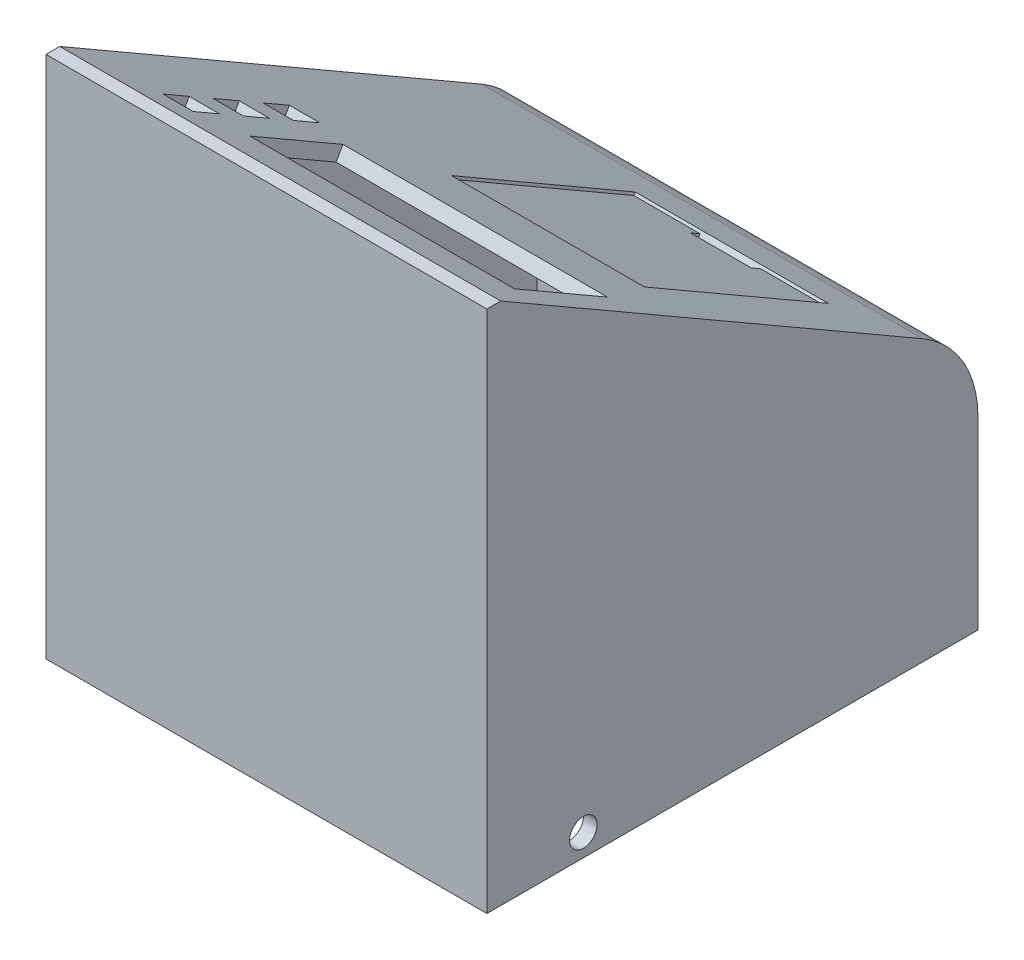
SolidWorks part; units mm, degrees
ref_plane "Front Plane" through (0, 0, 0) normal (0, 0, 1) x (1, 0, 0)
ref_plane "Top Plane" through (0, 0, 0) normal (0, 1, 0) x (1, 0, 0)
ref_plane "Right Plane" through (0, 0, 0) normal (1, 0, 0) x (0, 0, -1)
sketch "Sketch1" plane through (0, 0, 0) normal (1, 0, 0) x (0, 0, -1)
  line L0 (0, 0) -> (173.2051, -100)
  line L1 (173.2051, -100) -> (173.2051, -190)
  line L2 (173.2051, -190) -> (0, -190)
  line L3 (0, -190) -> (0, 0)
  line L4 (173.2051, -100) -> (290.6561, -100) construction
  dimension "D1" = 90
  dimension "D2" = 200
  dimension "D3" = 150
extrude "Boss-Extrude1" add sketch "Sketch1" along normal blind 5
ref_plane "Plane1" through (0, 0, 0) normal (0, 0.866, -0.5) x (1, 0, 0)
sketch "Sketch2" plane through (0, 0, 0) normal (0, 0.866, -0.5) x (1, 0, 0)
  line L0 (0, 200) -> (160, 200)
  line L1 (0, 200) -> (0, 0) construction
  line L2 (5, 200) -> (0, 200) construction
  line L3 (0, 200) -> (0, 0)
  line L4 (0, 0) -> (160, 0)
  line L5 (160, 0) -> (160, 200)
  dimension "D1" = 160
  dimension "D2" = 160
extrude "Boss-Extrude2" add sketch "Sketch2" against normal blind 5 contours L4 L5 L0 L3
ref_plane "Plane3" through (0, 0, 0) normal (0, 0, 1) x (1, 0, 0)
sketch "Sketch4" plane through (0, 0, 0) normal (0, 0, 1) x (1, 0, 0)
  line L0 (0, 0) -> (160, 0)
  line L1 (160, 0) -> (160, -190)
  line L2 (0, 0) -> (0, -190)
  line L3 (5, -190) -> (0, -190) construction
  line L4 (0, -190) -> (160, -190)
extrude "Boss-Extrude4" add sketch "Sketch4" along normal blind 5
ref_plane "Plane4" through (0, 0, -173.2051) normal (0, 0, -1) x (-1, 0, 0)
sketch "Sketch5" plane through (0, 0, -173.2051) normal (0, 0, -1) x (-1, 0, 0)
  line L0 (0, -100) -> (-160, -100)
  line L1 (-5, -100) -> (0, -100) construction
  line L2 (-160, -100) -> (-160, -190)
  line L3 (-160, -190) -> (0, -190)
  line L4 (0, -190) -> (0, -100)
extrude "Boss-Extrude5" add sketch "Sketch5" against normal blind 5
ref_plane "Plane5" through (70, 0, 0) normal (-1, 0, 0) x (0, 0, 1)
ref_plane "Plane6" through (80, 0, 0) normal (-1, 0, 0) x (0, 0, 1)
mirror "Mirror1" about plane through (80, 0, 0) normal (-1, 0, 0) of "Boss-Extrude1"
ref_plane "Plane7" through (0, 0, 0) normal (0, 0.866, -0.5) x (1, 0, 0)
sketch "Sketch6" plane through (0, 0, 0) normal (0, 0.866, -0.5) x (1, 0, 0)
  line L0 (0, 200) -> (0, 0) construction
  line L1 (160, 0) -> (0, 0) construction
  line L2 (160, 0) -> (160, 200) construction
  line L3 (160, 200) -> (0, 200) construction
  line L4 (0, 200) -> (0, 0) construction
  line L5 (160, 0) -> (0, 0) construction
  line L6 (160, 0) -> (160, 200) construction
  line L7 (160, 200) -> (0, 200) construction
  line L8 (34, 7.7765) -> (34, 64.7725) construction
  line L11 (54, 10) -> (150, 10) construction
  line L12 (150, 49) -> (150, 10) construction
  line L14 (54, 56.3152) -> (150, 56.3152)
  line L17 (28.5, 21.3152) -> (39.5, 21.3152)
  line L18 (28.5, 21.3152) -> (28.5, 10.3152)
  line L19 (28.5, 10.3152) -> (39.5, 10.3152)
  line L20 (39.5, 21.3152) -> (39.5, 10.3152)
  line L21 (28.5, 21.3152) -> (39.5, 10.3152) construction
  line L22 (28.5, 10.3152) -> (39.5, 21.3152) construction
  line L23 (28.5, 42.3152) -> (39.5, 42.3152)
  line L24 (28.5, 42.3152) -> (28.5, 31.3152)
  line L25 (28.5, 31.3152) -> (39.5, 31.3152)
  line L26 (39.5, 42.3152) -> (39.5, 31.3152)
  line L27 (28.5, 42.3152) -> (39.5, 31.3152) construction
  line L28 (28.5, 31.3152) -> (39.5, 42.3152) construction
  line L29 (28.5, 63.3152) -> (39.5, 63.3152)
  line L30 (28.5, 63.3152) -> (28.5, 52.3152)
  line L31 (28.5, 52.3152) -> (39.5, 52.3152)
  line L32 (39.5, 63.3152) -> (39.5, 52.3152)
  line L33 (28.5, 63.3152) -> (39.5, 52.3152) construction
  line L34 (28.5, 52.3152) -> (39.5, 63.3152) construction
  line L35 (54, 56.3152) -> (54, 17.3152)
  line L36 (54, 17.3152) -> (150, 17.3152)
  line L37 (150, 56.3152) -> (150, 17.3152)
  line L38 (54, 56.3152) -> (150, 17.3152) construction
  line L39 (54, 17.3152) -> (150, 56.3152) construction
  point P6 (102, 36.8152)
  point P11 (34, 15.8152)
  point P17 (34, 36.8152)
  point P22 (34, 57.8152)
  dimension "D2" = 96
  dimension "D3" = 10
  dimension "D4" = 10
  dimension "D5" = 39
  dimension "D6" = 11
  dimension "D7" = 11
  dimension "D8" = 11
  dimension "D9" = 11
  dimension "D10" = 10
  dimension "D11" = 10
extrude "Cut-Extrude2" cut sketch "Sketch6" against normal blind 5
fillet "Fillet1" radius 40 1 edges at (80, -100, -173.2051)
sketch "Sketch7" plane through (0, 0, 0) normal (0, 0.866, -0.5) x (1, 0, 0)
  line L0 (34, 63.3152) -> (160, 63.3152) construction
  line L1 (39.5, 63.3152) -> (28.5, 63.3152) construction
  line L2 (160, 0) -> (160, 176.906) construction
  line L4 (70, 160.3152) -> (140, 160.3152)
  line L5 (70, 160.3152) -> (70, 83.3152)
  line L6 (70, 83.3152) -> (140, 83.3152)
  line L7 (140, 160.3152) -> (140, 83.3152)
  line L8 (70, 160.3152) -> (140, 83.3152) construction
  line L9 (70, 83.3152) -> (140, 160.3152) construction
  point P6 (105, 121.8152)
  dimension "D1" = 70
  dimension "D2" = 77
  dimension "D3" = 20
  dimension "D4" = 20
extrude "Cut-Extrude3" cut sketch "Sketch7" against normal blind 1
sketch "Sketch8" plane through (0, -0.866, 0.5) normal (0, 0.866, -0.5) x (1, 0, 0)
  line L1 (140, 160.3152) -> (70, 160.3152) construction
  line L2 (94, 160.3152) -> (116, 160.3152)
  line L3 (94, 160.3152) -> (94, 156.3152)
  line L4 (94, 156.3152) -> (116, 156.3152)
  line L5 (116, 160.3152) -> (116, 156.3152)
  line L6 (94, 160.3152) -> (116, 156.3152) construction
  line L7 (94, 156.3152) -> (116, 160.3152) construction
  line L9 (70, 160.3152) -> (70, 83.3152) construction
  point P4 (105, 158.3152)
  point P9 (105, 160.3152)
  dimension "D1" = 22
  dimension "D2" = 4
  dimension "D3" = 0
  dimension "D4" = 35
extrude "Cut-Extrude4" cut sketch "Sketch8" against normal blind 4
sketch "Sketch9" plane through (0, 0, 0) normal (0, 0.866, -0.5) x (1, 0, 0)
  line L0 (160, 176.906) -> (0, 176.906) construction
  line L1 (0, 176.906) -> (0, 0) construction
  line L2 (160, 176.906) -> (0, 176.906) construction
  line L3 (0, 176.906) -> (0, 0) construction
  line L5 (15, 151.8152) -> (55, 151.8152)
  line L6 (15, 151.8152) -> (15, 91.8152)
  line L7 (15, 91.8152) -> (55, 91.8152)
  line L8 (55, 151.8152) -> (55, 91.8152)
  line L9 (15, 151.8152) -> (55, 91.8152) construction
  line L10 (15, 91.8152) -> (55, 151.8152) construction
  line L12 (70, 83.3152) -> (11.8162, 83.3152) construction
  point P2 (35, 121.8152)
  dimension "D1" = 40
  dimension "D2" = 60
  dimension "D3" = 15
  dimension "D4" = 8.5
extrude "Cut-Extrude5" cut sketch "Sketch9" against normal blind 5
sketch "Sketch12" plane through (0, 0, 0) normal (0, 0.866, -0.5) x (1, 0, 0)
  line L0 (55, 91.8152) -> (55, 151.8152) construction
  line L1 (15, 91.8152) -> (55, 91.8152) construction
  line L2 (15, 151.8152) -> (15, 91.8152) construction
  line L3 (55, 151.8152) -> (15, 151.8152) construction
  line L4 (55, 91.8152) -> (55, 151.8152)
  line L5 (15, 91.8152) -> (55, 91.8152)
  line L6 (15, 151.8152) -> (15, 91.8152)
  line L7 (55, 151.8152) -> (15, 151.8152)
extrude "Boss-Extrude6" add sketch "Sketch12" against normal blind 2
ref_plane "Plane8" through (0, 0, -173.2051) normal (0, 0, -1) x (-1, 0, 0)
sketch "Sketch14" plane through (0, 0, -173.2051) normal (0, 0, -1) x (-1, 0, 0)
  line L0 (0, -123.094) -> (-160, -123.094) construction
  line L1 (-140, -130.094) -> (-63, -130.094)
  line L2 (-140, -130.094) -> (-140, -183.094)
  line L3 (-140, -183.094) -> (-63, -183.094)
  line L4 (-63, -130.094) -> (-63, -183.094)
  line L5 (-140, -130.094) -> (-63, -183.094) construction
  line L6 (-140, -183.094) -> (-63, -130.094) construction
  line L7 (0, -123.094) -> (-160, -123.094) construction
  line L8 (-160, -190) -> (0, -190) construction
  line L9 (-160, -190) -> (0, -190) construction
  line L10 (0, -190) -> (0, -123.094) construction
  line L11 (0, -190) -> (0, -123.094) construction
  line L12 (-160, -123.094) -> (-160, -190) construction
  point P0 (-101.5, -156.594)
  dimension "D1" = 77
  dimension "D2" = 53
  dimension "D3" = 20
  dimension "D4" = 7
extrude "Cut-Extrude6" cut sketch "Sketch14" against normal blind 5
sketch "Sketch15" plane through (0, 0, -173.2051) normal (0, 0, -1) x (-1, 0, 0)
  line L0 (-63, -130.094) -> (-31.075, -130.094) construction
  line L1 (-63, -142.094) -> (-31.075, -142.094) construction
  line L2 (-63, -183.094) -> (-63, -130.094) construction
  line L3 (-63, -183.094) -> (-31.075, -183.094) construction
  line L4 (-63, -171.094) -> (-31.075, -171.094) construction
  line L5 (-63, -142.094) -> (-60, -142.094)
  line L6 (-60, -142.094) -> (-60, -171.094)
  line L7 (-60, -171.094) -> (-63, -171.094)
  line L8 (-63, -171.094) -> (-63, -142.094)
  line L15 (-140, -171.094) -> (-140, -142.094)
  line L16 (-143, -142.094) -> (-143, -171.094)
  line L17 (-143, -171.094) -> (-140, -171.094)
  line L18 (-140, -142.094) -> (-143, -142.094)
  dimension "D1" = 12
  dimension "D2" = 12
  dimension "D3" = 3
extrude "Cut-Extrude7" cut sketch "Sketch15" against normal blind 5
ref_plane "Plane9" through (0, -4.3301, 2.5) normal (0, -0.866, 0.5) x (-1, 0, 0)
sketch "Sketch17" plane through (0, -4.3301, 2.5) normal (0, -0.866, 0.5) x (-1, 0, 0)
  line L0 (-160, 0) -> (-160, 176.906) construction
  line L1 (-53, 66.7395) -> (-151, 66.7395) construction
  line L2 (-53, 66.7395) -> (-53, 6.7395) construction
  line L3 (-53, 6.7395) -> (-151, 6.7395) construction
  line L4 (-151, 66.7395) -> (-151, 6.7395) construction
  line L5 (-53, 66.7395) -> (-151, 6.7395) construction
  line L6 (-53, 6.7395) -> (-151, 66.7395) construction
  circle A0 centre (-54.75, 64.9895) radius 1.75
  circle A2 centre (-149.25, 64.9895) radius 1.75
  circle A3 centre (-54.75, 8.4895) radius 1.75
  circle A4 centre (-149.25, 8.4895) radius 1.75
  point P0 (-102, 36.7395)
  dimension "D6" = 3.5
  dimension "D1" = 98
  dimension "D2" = 60
  dimension "D3" = 9
  dimension "D4" = 1.75
  dimension "D5" = 1.75
extrude "Cut-Extrude9" cut sketch "Sketch17" against normal blind 4
ref_plane "Plane10" through (0, -1.7321, 1) normal (0, -0.866, 0.5) x (-1, 0, 0)
sketch "Sketch21" plane through (0, -1.7321, 1) normal (0, -0.866, 0.5) x (-1, 0, 0)
  line L0 (-55, 91.8152) -> (-55, 151.8152) construction
  line L1 (-15, 151.8152) -> (-15, 91.8152) construction
  line L2 (-55, 151.8152) -> (-15, 151.8152) construction
  line L3 (-55, 91.8152) -> (-55, 151.8152) construction
  line L4 (-15, 151.8152) -> (-15, 91.8152) construction
  line L5 (-55, 151.8152) -> (-15, 151.8152) construction
  line L6 (-55, 91.8152) -> (-15, 91.8152) construction
  circle A0 centre (-48.5, 98.3152) radius 1.5
  circle A1 centre (-21.5, 97.3152) radius 1.5
  circle A2 centre (-17.5, 136.3152) radius 1.5
  circle A4 centre (-52.5, 136.3152) radius 1.5
  dimension "D1" = 3
  dimension "D4" = 3
  dimension "D7" = 3
  dimension "D2" = 6.5
  dimension "D3" = 6.5
  dimension "D5" = 6.5
  dimension "D6" = 5.5
  dimension "D8" = 2.5
  dimension "D9" = 15.5
extrude "Boss-Extrude8" add sketch "Sketch21" along normal blind 4
ref_plane "Plane11" through (0, -190, 0) normal (0, -1, 0) x (-1, 0, 0)
sketch "Sketch23" plane through (0, -190, 0) normal (0, -1, 0) x (-1, 0, 0)
  line L0 (-155, 0) -> (-148.5035, 7.6023) construction
  line L1 (-155, 0) -> (-145, 0)
  line L2 (-155, 0) -> (-155, 10)
  arc A0 (-145, 0) -> (-155, 10) centre (-155, 0) ccw
  circle A1 centre (-151.7517, 3.8012) radius 1.5
  dimension "D1" = 3
  dimension "D2" = 20
extrude "Boss-Extrude9" add sketch "Sketch23" against normal blind 10
mirror "Mirror2" about plane through (80, 0, 0) normal (-1, 0, 0) of "Boss-Extrude9"
sketch "Sketch25" plane through (0, -190, 0) normal (0, -1, 0) x (-1, 0, 0)
  line L0 (-155, 168.2051) -> (-148.2405, 160.8356) construction
  line L1 (-155, 168.2051) -> (-145, 168.2051)
  line L2 (-155, 168.2051) -> (-155, 158.2051)
  arc A0 (-155, 158.2051) -> (-145, 168.2051) centre (-155, 168.2051) ccw
  circle A1 centre (-151.6203, 164.5203) radius 1.5
  dimension "D1" = 20
  dimension "D2" = 3
extrude "Boss-Extrude10" add sketch "Sketch25" against normal blind 10
mirror "Mirror4" about plane through (80, 0, 0) normal (-1, 0, 0) of "Boss-Extrude10"
sketch "Sketch33" plane through (160, 0, 0) normal (1, 0, 0) x (0, 0, -1)
  line L0 (-5, -190) -> (173.2051, -190) construction
  line L1 (-5, -190) -> (-5, 0) construction
  circle A0 centre (30, -182) radius 5
  dimension "D1" = 10
  dimension "D2" = 8
  dimension "D3" = 35
extrude "Cut-Extrude14" cut sketch "Sketch33" against normal blind 10
